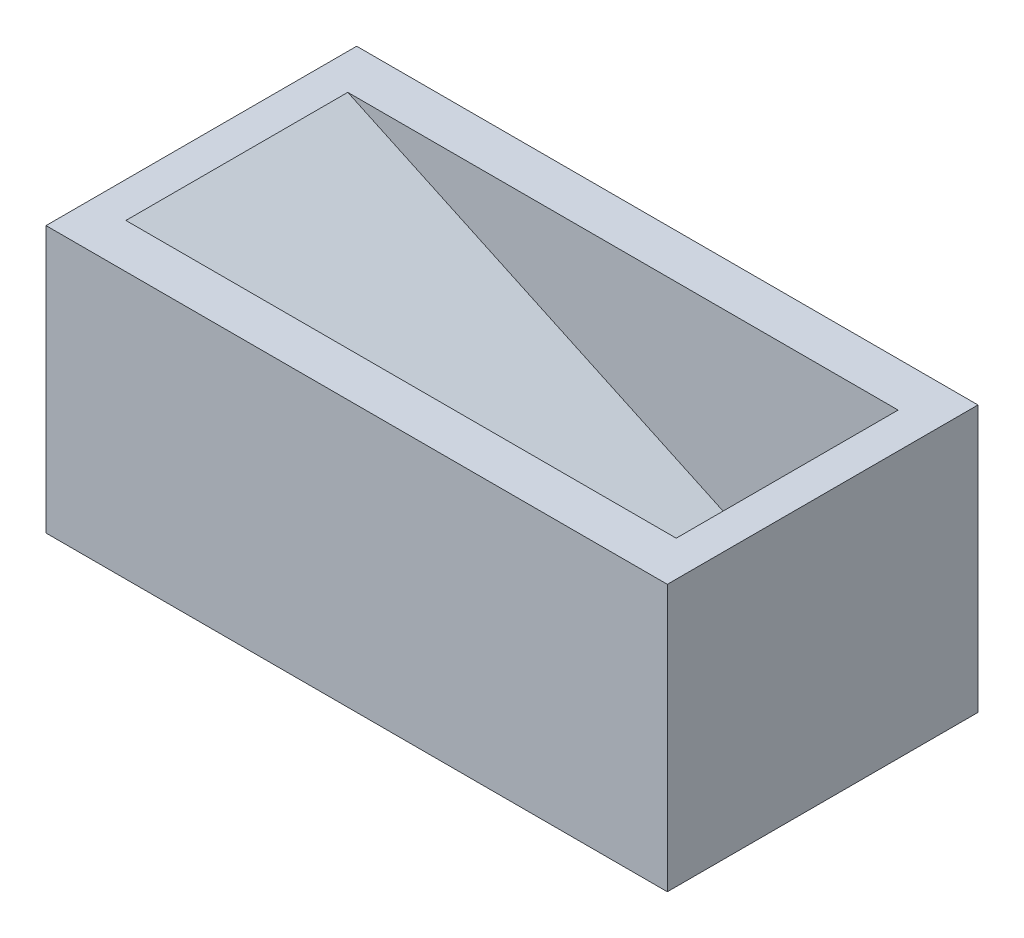
SolidWorks part; units mm, degrees
ref_plane "Front" through (0, 0, 0) normal (0, 0, 1) x (1, 0, 0)
ref_plane "Top" through (0, 0, 0) normal (0, 1, 0) x (1, 0, 0)
ref_plane "Right" through (0, 0, 0) normal (1, 0, 0) x (0, 0, -1)
sketch "Sketch1" plane through (0, 0, 0) normal (0, 1, 0) x (1, 0, 0)
  line L1 (-17.5, 8.75) -> (17.5, 8.75)
  line L2 (-17.5, 8.75) -> (-17.5, -8.75)
  line L3 (-17.5, -8.75) -> (17.5, -8.75)
  line L4 (17.5, 8.75) -> (17.5, -8.75)
  line L5 (-17.5, 8.75) -> (17.5, -8.75) construction
  line L6 (-17.5, -8.75) -> (17.5, 8.75) construction
  point P0 (0, 0)
  dimension "D1" = 35
  dimension "D2" = 17.5
extrude "Boss-Extrude2" add sketch "Sketch1" along normal mid plane 15 contours L1 L4 L3 L2
sketch "Sketch2" plane through (0, 0, 8.75) normal (0, 0, 1) x (1, 0, 0)
  line L0 (-17.5, 7.5) -> (-17.5, -7.5) construction
  line L1 (-17.5, 36.5) -> (17.5, 36.5)
  line L2 (-17.5, 36.5) -> (-17.5, 12.5)
  line L3 (-17.5, 12.5) -> (17.5, 12.5)
  line L4 (17.5, 36.5) -> (17.5, 12.5)
  line L5 (17.5, 7.5) -> (17.5, -7.5) construction
  line L6 (-17.5, -7.5) -> (17.5, -7.5) construction
  dimension "D1" = 20
  dimension "D2" = 24
extrude "Cut-Extrude1" [suppressed] cut sketch "Sketch2" against normal blind 12.5
sketch "Sketch3" [suppressed] plane through (0, 0, 0) normal (0, 0, 1) x (1, 0, 0)
  line L0 (-3.75, 6.5) -> (-3.75, 1.25)
  line L1 (12.5, 6.5) -> (-12.5, 6.5) construction
  line L2 (-3.75, 1.25) -> (0.75, 1.25)
  line L3 (0.75, 1.25) -> (0.75, -1.25)
  line L4 (0.75, -1.25) -> (-3.75, -1.25)
  line L5 (-3.75, -1.25) -> (-3.75, -17.5)
  line L6 (-12.5, -17.5) -> (12.5, -17.5) construction
  line L7 (-3.75, -17.5) -> (12.5, -17.5)
  line L8 (12.5, -17.5) -> (12.5, 6.5)
  line L9 (12.5, 6.5) -> (-3.75, 6.5)
  dimension "D1" = 5.25
  dimension "D2" = 2.5
  dimension "D3" = 16.25
  dimension "D4" = 4.5
extrude "Boss-Extrude3" [suppressed] add sketch "Sketch3" along normal blind 12.5
sketch "Sketch5" plane through (0, 0, 0) normal (0, 0, 1) x (1, 0, 0)
  line L11 (-15.5, 7.5) -> (9.9632, -4.3737)
  line L14 (-15.5, 7.5) -> (15.5, 7.5)
  line L15 (-17.5, 7.5) -> (17.5, 7.5) construction
  line L16 (9.9632, -4.3737) -> (15.5, 7.5)
  line L18 (17.5, 7.5) -> (17.5, -7.5) construction
  dimension "D1" = 2
  dimension "D2" = 2
  dimension "D3" = 25
extrude "Cut-Extrude2" cut sketch "Sketch5" against normal mid plane 12.5
